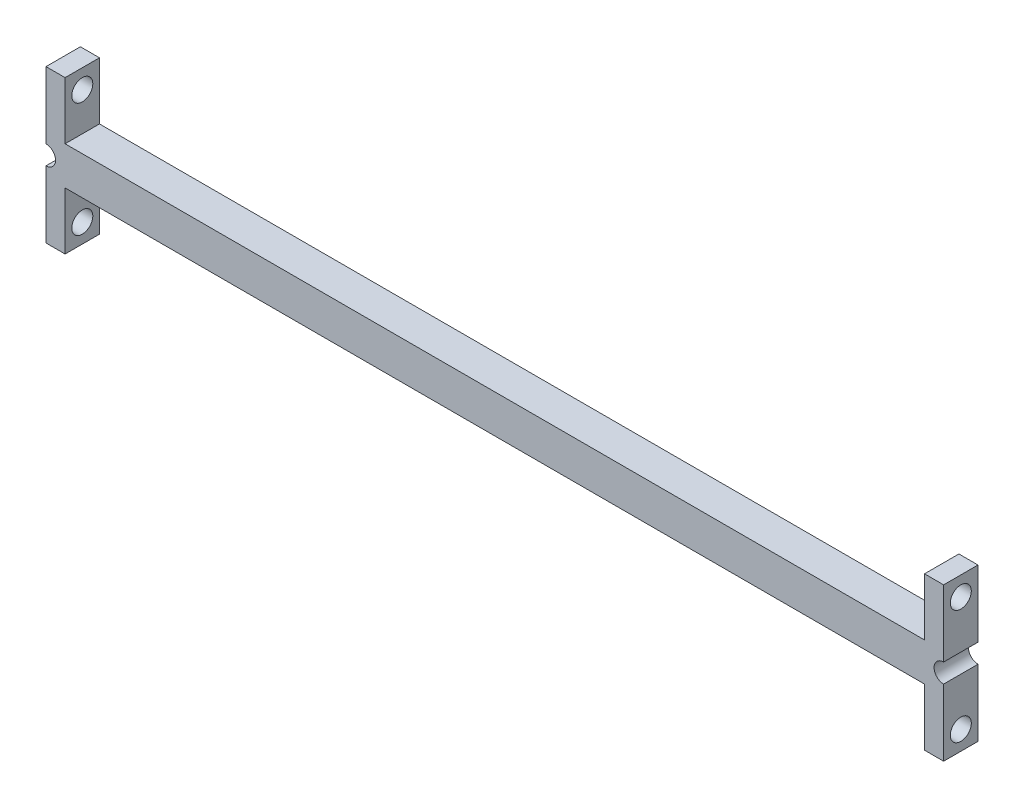
SolidWorks part; units mm, degrees
ref_plane "前视基准面" through (0, 0, 0) normal (0, 0, 1) x (1, 0, 0)
ref_plane "上视基准面" through (0, 0, 0) normal (0, 1, 0) x (1, 0, 0)
ref_plane "右视基准面" through (0, 0, 0) normal (1, 0, 0) x (0, 0, -1)
other "Configuration Table"
sketch "草图1" plane through (0, 0, 0) normal (0, 0, 1) x (1, 0, 0)
  line L1 (0, 0) -> (235, 0)
  line L2 (0, 0) -> (0, -10)
  line L3 (0, -10) -> (235, -10)
  line L4 (235, 0) -> (235, -10)
  dimension "D1" = 235
  dimension "D2" = 10
extrude "凸台-拉伸1" add sketch "草图1" along normal blind 9
sketch "草图2" plane through (0, 0, 9) normal (0, 0, 1) x (1, 0, 0)
  line L1 (230, 15) -> (235, 15)
  line L2 (230, 15) -> (230, -25)
  line L3 (230, -25) -> (235, -25)
  line L4 (235, 15) -> (235, -25)
  line L5 (0, 15) -> (5, 15)
  line L6 (0, 15) -> (0, -25)
  line L7 (0, -25) -> (5, -25)
  line L8 (5, 15) -> (5, -25)
  line L9 (235, -10) -> (235, 0) construction
  line L10 (0, 0) -> (0, -10) construction
  line L11 (235, 0) -> (0, 0) construction
  line L12 (0, -10) -> (235, -10) construction
  dimension "D1" = 15
  dimension "D2" = 15
  dimension "D3" = 5
  dimension "D4" = 15
  dimension "D5" = 15
  dimension "D6" = 5
extrude "凸台-拉伸2" add sketch "草图2" against normal blind 9
sketch "草图3" plane through (0, 0, 9) normal (0, 0, 1) x (1, 0, 0)
  line L0 (235, -25) -> (235, 15) construction
  line L1 (0, 15) -> (0, -25) construction
  circle A0 centre (235, -5) radius 2.5
  circle A1 centre (0, -5) radius 2.5
  dimension "D1" = 5
  dimension "D2" = 5
extrude "切除-拉伸1" cut sketch "草图3" against normal blind 32
sketch "草图4" plane through (0, 0, 0) normal (-1, 0, 0) x (0, 0, 1)
  line L0 (4.5, 12.3561) -> (4.5, -22.0434) construction
  line L1 (9, -7.5) -> (9, -25) construction
  line L2 (0, -7.5) -> (0, -25) construction
  line L3 (-7.6668, -5) -> (20.6936, -5) construction
  line L4 (0, -25) -> (9, -25) construction
  line L5 (0, 15) -> (9, 15) construction
  circle A0 centre (4.5, 10) radius 2.75
  circle A1 centre (4.5, -20) radius 2.75
  point P16 (0, 0)
  dimension "D1" = 5.5
  dimension "D2" = 5
extrude "切除-拉伸2" cut sketch "草图4" against normal through all contours A0 | A1
